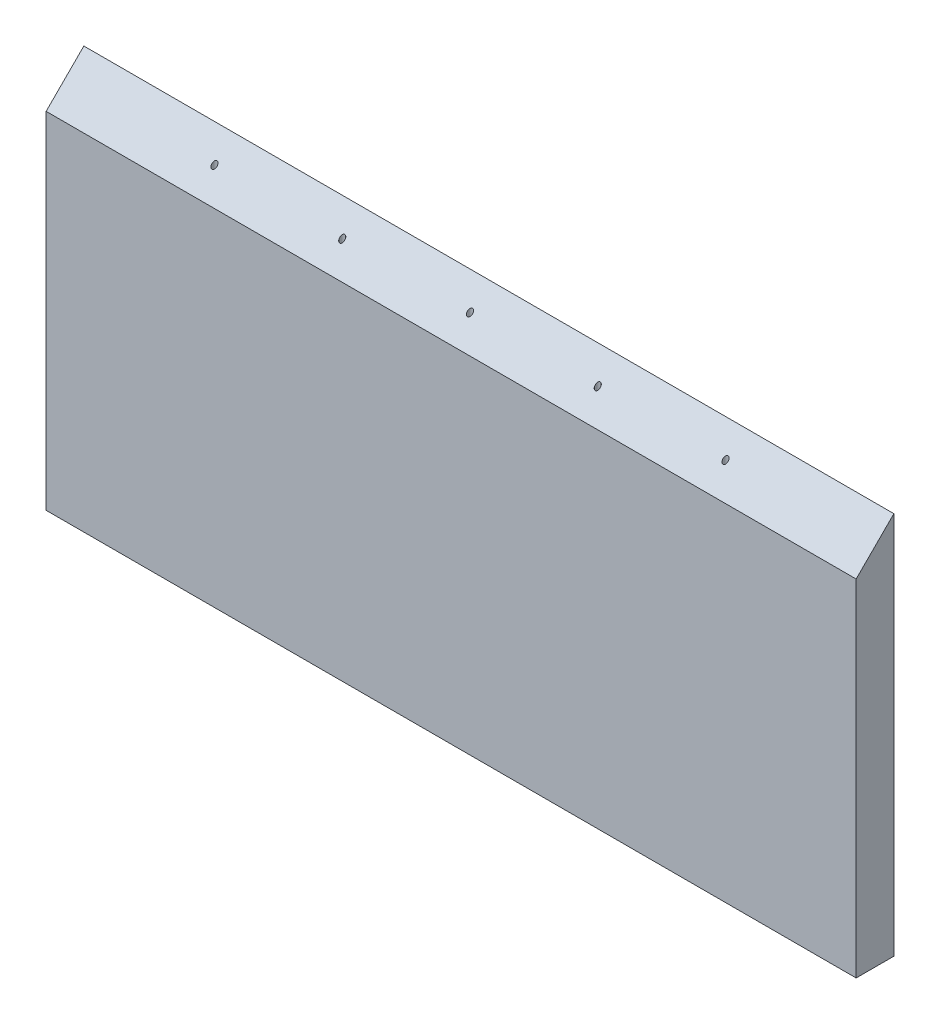
SolidWorks part; units mm, degrees
material "轻木"
ref_plane "Front" through (0, 0, 0) normal (0, 0, 1) x (1, 0, 0)
ref_plane "Top" through (0, 0, 0) normal (0, 1, 0) x (1, 0, 0)
ref_plane "Right" through (0, 0, 0) normal (1, 0, 0) x (0, 0, -1)
sketch "草图1" plane through (0, 0, 0) normal (0, 0, 1) x (1, 0, 0)
  line L1 (0, 0) -> (322.1, 0)
  line L2 (0, 0) -> (0, 152.4)
  line L3 (0, 152.4) -> (322.1, 152.4)
  line L4 (322.1, 0) -> (322.1, 152.4)
  dimension "D1" = 322.1
  dimension "D2" = 152.4
extrude "凸台-拉伸1" add sketch "草图1" along normal blind 15
sketch "草图2" plane through (0, 0, 0) normal (0, 1, 0) x (1, 0, 0)
  line L0 (161.05, 36.6636) -> (161.05, 14.162) construction
  line L1 (0, -15) -> (0, 0) construction
  line L2 (322.1, -15) -> (322.1, 0) construction
  line L3 (33.9328, -7.5) -> (83.9737, -7.5) construction
  line L4 (322.1, 0) -> (0, 0) construction
  line L5 (322.1, -15) -> (0, -15) construction
  circle A0 centre (161.05, -7.5) radius 1
  circle A1 centre (211.85, -7.5) radius 1
  circle A2 centre (262.65, -7.5) radius 1
  circle A3 centre (110.25, -7.5) radius 1
  circle A4 centre (59.45, -7.5) radius 1
  dimension "D1" = 2
  dimension "D2" = 3
  dimension "D3" = 3
extrude "切除-拉伸1" cut sketch "草图2" against normal blind 50.8 from surface at 152.4 starting at face at (161.05, 152.4, 7.5)
sketch "草图3" plane through (0, 0, 0) normal (-1, 0, 0) x (0, 0, 1)
  line L0 (0, 152.4) -> (15, 137.4)
  line L1 (15, 152.4) -> (15, 0) construction
  line L2 (15, 137.4) -> (15, 152.4)
  line L3 (15, 152.4) -> (0, 152.4)
  dimension "D1" = 15
extrude "切除-拉伸2" cut sketch "草图3" against normal through all
